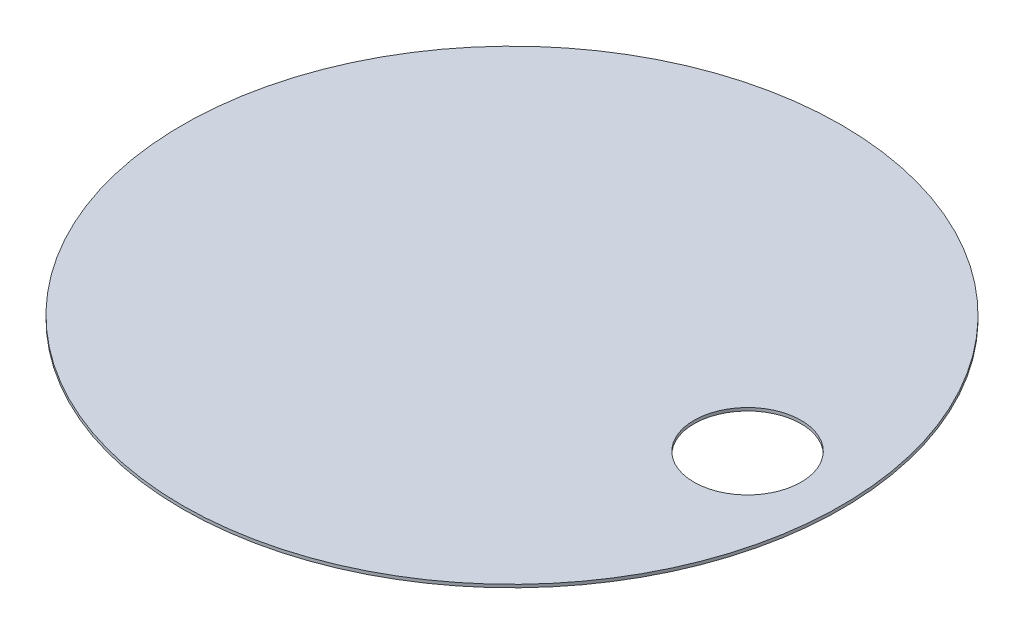
SolidWorks part; units mm, degrees
ref_plane "前视基准面" through (0, 0, 0) normal (0, 0, 1) x (1, 0, 0)
ref_plane "上视基准面" through (0, 0, 0) normal (0, 1, 0) x (1, 0, 0)
ref_plane "右视基准面" through (0, 0, 0) normal (1, 0, 0) x (0, 0, -1)
other "Configuration Table"
sketch "草图1" plane through (0, 0, 0) normal (0, 1, 0) x (1, 0, 0)
  circle A0 centre (0, 0) radius 326
  dimension "D1" = 652
extrude "凸台-拉伸1" add sketch "草图1" along normal mid plane 3
sketch "草图3" plane through (0, 0, 0) normal (0, 1, 0) x (1, 0, 0)
  circle A0 centre (0, 0) radius 10
  dimension "D1" = 20
extrude "凸台-拉伸2" add sketch "草图3" against normal blind 6
sketch "草图4" plane through (0, 0, 0) normal (0, 1, 0) x (1, 0, 0)
  line L0 (0, 0) -> (254.4035, 0) construction
  circle A0 centre (233, 0) radius 53
  point P5 (111.0284, 0)
  dimension "D2" = 106
  dimension "D1" = 233
extrude "切除-拉伸1" cut sketch "草图4" against normal through all both and the other way through all
